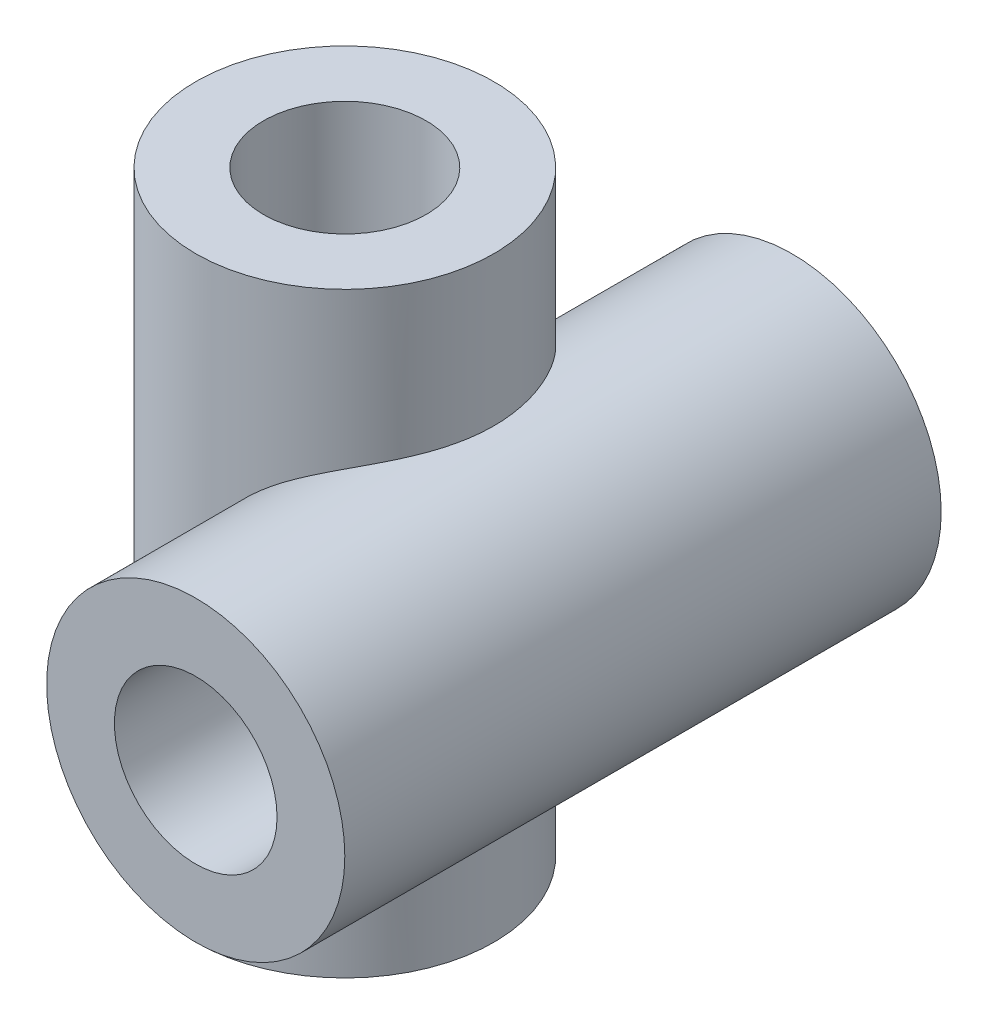
SolidWorks part; units mm, degrees
ref_plane "Front Plane" through (0, 0, 0) normal (0, 0, 1) x (1, 0, 0)
ref_plane "Top Plane" through (0, 0, 0) normal (0, 1, 0) x (1, 0, 0)
ref_plane "Right Plane" through (0, 0, 0) normal (1, 0, 0) x (0, 0, -1)
sketch "Sketch1" plane through (0, 0, 0) normal (0, 1, 0) x (1, 0, 0)
  line L0 (0, 42.1337) -> (0, -43.4019) construction
  line L1 (-53.8297, 0) -> (47.2067, 0) construction
  circle A0 centre (0, 0) radius 27.5
  dimension "D1" = 55
extrude "Boss-Extrude2" add sketch "Sketch1" along normal blind 110
sketch "Sketch2" plane through (0, 0, 0) normal (0, 0, 1) x (1, 0, 0)
  line L0 (27.5, 0) -> (27.5, 110) construction
  line L1 (27.5, 110) -> (-27.5, 110) construction
  circle A0 centre (27.5, 55) radius 27.5
  dimension "D2" = 55
  dimension "D1" = 55
extrude "Boss-Extrude3" add sketch "Sketch2" along normal mid plane 110
sketch "Sketch3" plane through (0, 110, 0) normal (0, 1, 0) x (1, 0, 0)
  circle A0 centre (0, 0) radius 15
extrude "Cut-Extrude1" cut sketch "Sketch3" against normal blind 110
sketch "Sketch5" plane through (0, 0, 55) normal (0, 0, 1) x (1, 0, 0)
  circle A0 centre (27.5, 55) radius 15
extrude "Cut-Extrude2" cut sketch "Sketch5" against normal blind 110
